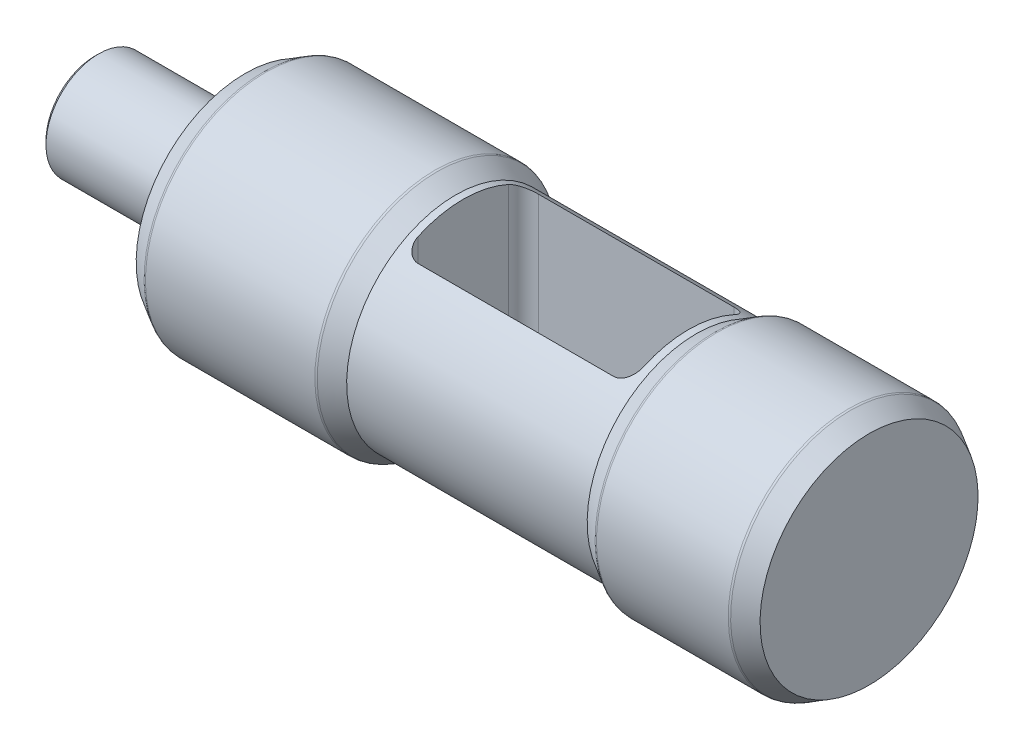
SolidWorks part; units mm, degrees
material "Простая углеродистая сталь"
ref_plane "Спереди" through (0, 0, 0) normal (0, 0, 1) x (1, 0, 0)
ref_plane "Сверху" through (0, 0, 0) normal (0, 1, 0) x (1, 0, 0)
ref_plane "Справа" through (0, 0, 0) normal (1, 0, 0) x (0, 0, -1)
sketch "Эскиз1" plane through (0, 0, 0) normal (0, 0, 1) x (1, 0, 0)
  line L0 (0, 0) -> (-214.9415, 0) construction
  line L1 (0, 0) -> (0, 14.5)
  line L2 (0, 14.5) -> (-2.4821, 15.933)
  line L3 (-2.7321, 16) -> (-20.2679, 16)
  line L4 (-20.5179, 15.933) -> (-23, 14.5)
  line L5 (-23, 14.5) -> (-55, 14.5)
  line L6 (-55, 14.5) -> (-57.4821, 15.933)
  line L7 (-57.7321, 16) -> (-80.2679, 16)
  line L8 (-80.5179, 15.933) -> (-83, 14.5)
  line L9 (-83, 14.5) -> (-83, 7)
  line L10 (-83, 7) -> (-102.5, 7)
  line L11 (-103, 6.5) -> (-103, 0)
  line L12 (-103, 0) -> (0, 0)
  line L13 (-102.5, 7) -> (-103, 6.5)
  arc A0 (-80.2679, 16) -> (-80.5179, 15.933) centre (-80.2679, 15.5) ccw
  arc A1 (-57.4821, 15.933) -> (-57.7321, 16) centre (-57.7321, 15.5) ccw
  arc A2 (-2.4821, 15.933) -> (-2.7321, 16) centre (-2.7321, 15.5) ccw
  arc A3 (-20.2679, 16) -> (-20.5179, 15.933) centre (-20.2679, 15.5) ccw
  point P13 (-103, 7)
  dimension "D11" = 0.5
  dimension "D1" = 20
  dimension "D2" = 30
  dimension "D3" = 29
  dimension "D4" = 32
  dimension "D5" = 14
  dimension "D6" = 28
  dimension "D7" = 103
  dimension "D8" = 32
  dimension "D9" = 0.5
  dimension "D10" = 45
revolve "Повернуть1" add sketch "Эскиз1" angle 360 about L0
sketch "Эскиз2" plane through (0, 0, 0) normal (0, 1, 0) x (1, 0, 0)
  line L0 (-23, -14.5) -> (-23, 14.5) construction
  line L1 (-52, -8) -> (-26, -8)
  line L2 (-54, -6) -> (-54, 6)
  line L3 (-52, 8) -> (-26, 8)
  line L4 (-24, -6) -> (-24, 6)
  line L5 (-55, -14.5) -> (-55, 14.5) construction
  arc A0 (-54, 6) -> (-52, 8) centre (-52, 6) cw
  arc A1 (-52, -8) -> (-54, -6) centre (-52, -6) cw
  arc A2 (-26, -8) -> (-24, -6) centre (-26, -6) ccw
  arc A3 (-26, 8) -> (-24, 6) centre (-26, 6) cw
  point P4 (-54, 0)
  point P16 (-24, -8)
  point P19 (-24, 8)
  dimension "D4" = 2
  dimension "D1" = 1
  dimension "D2" = 16
  dimension "D3" = 1
extrude "Вырез-Вытянуть1" cut sketch "Эскиз2" against normal through all and the other way through all
